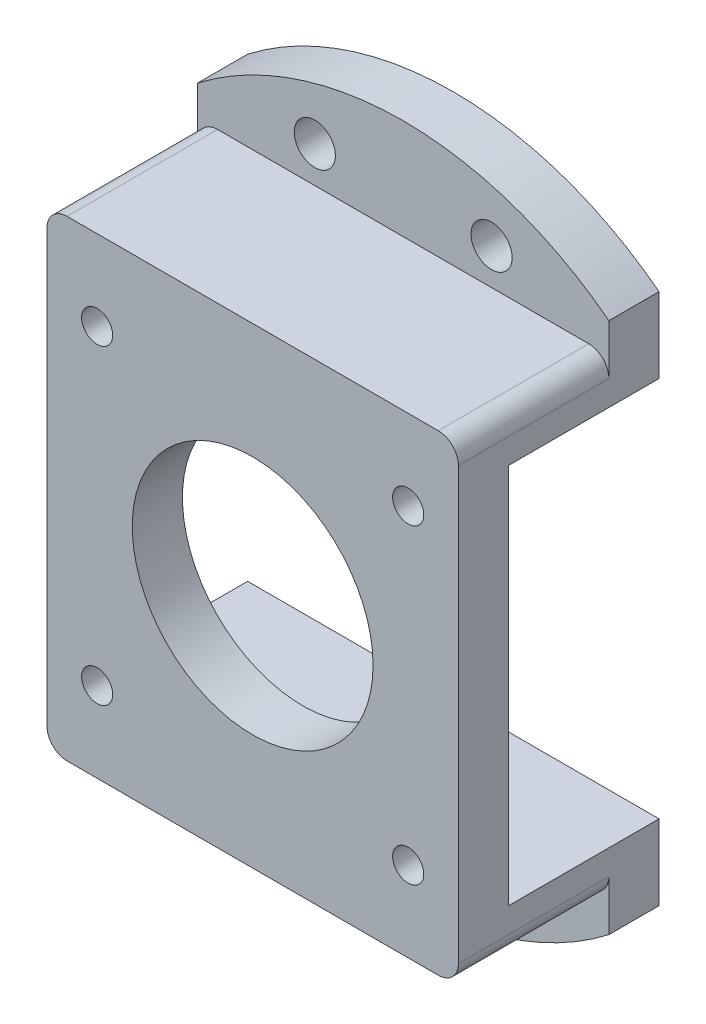
SolidWorks part; units mm, degrees
ref_plane "Front Plane" through (0, 0, 0) normal (0, 0, 1) x (1, 0, 0)
ref_plane "Top Plane" through (0, 0, 0) normal (0, 1, 0) x (1, 0, 0)
ref_plane "Right Plane" through (0, 0, 0) normal (1, 0, 0) x (0, 0, -1)
sketch "Sketch1" plane through (0, 0, 0) normal (0, 0, 1) x (1, 0, 0)
  line L1 (-15.5, -15.5) -> (15.5, -15.5) construction
  line L2 (-15.5, -15.5) -> (-15.5, 15.5) construction
  line L3 (-15.5, 15.5) -> (15.5, 15.5) construction
  line L4 (15.5, -15.5) -> (15.5, 15.5) construction
  line L5 (-15.5, -15.5) -> (15.5, 15.5) construction
  line L6 (-15.5, 15.5) -> (15.5, -15.5) construction
  line L7 (-20.5, -19) -> (20.5, -19)
  line L8 (-20.5, -19) -> (-20.5, 19)
  line L9 (-20.5, 19) -> (20.5, 19)
  line L10 (20.5, -19) -> (20.5, 19)
  line L11 (-20.5, -19) -> (20.5, 19) construction
  line L12 (-20.5, 19) -> (20.5, -19) construction
  circle A0 centre (15.5, 15.5) radius 1.55
  circle A1 centre (-15.5, 15.5) radius 1.55
  circle A2 centre (15.5, -15.5) radius 1.55
  circle A3 centre (-15.5, -15.5) radius 1.55
  circle A4 centre (-15.5, 15.5) radius 2.8 construction
  circle A7 centre (0, 0) radius 12
  point P0 (0, 0)
  point P10 (0, 0)
  dimension "D2" = 3.1
  dimension "D3" = 3.1
  dimension "D4" = 3.1
  dimension "D5" = 3.1
  dimension "D7" = 5.6
  dimension "D8" = 38
  dimension "D9" = 24
  dimension "D1" = 31
  dimension "D6" = 41
extrude "Boss-Extrude1" add sketch "Sketch1" along normal blind 5 contours L7 L10 L9 L8 A4 A3 A2 A0
sketch "Sketch2" plane through (0, 0, 5) normal (0, 0, 1) x (1, 0, 0)
  line L8 (20.5, -19) -> (20.5, 19) construction
  line L9 (-20.5, 19) -> (20.5, 19)
  line L10 (-20.5, 19) -> (-20.5, 23.5)
  line L11 (-20.5, 23.5) -> (20.5, 23.5)
  line L12 (20.5, 19) -> (20.5, 23.5)
  line L13 (-20.5, 19) -> (20.5, 23.5) construction
  line L14 (-20.5, 23.5) -> (20.5, 19) construction
  line L15 (-20.5, 19) -> (20.5, 19) construction
  line L17 (-20.5, -19) -> (20.5, -19)
  line L18 (-20.5, -19) -> (-20.5, -23.5)
  line L19 (-20.5, -23.5) -> (20.5, -23.5)
  line L20 (20.5, -19) -> (20.5, -23.5)
  line L21 (-20.5, -19) -> (20.5, -23.5) construction
  line L22 (-20.5, -23.5) -> (20.5, -19) construction
  point P5 (0, 21.25)
  point P16 (0, -21.25)
  dimension "D1" = 4.5
  dimension "D2" = 4.5
extrude "Boss-Extrude2" add sketch "Sketch2" against normal blind 20
sketch "Sketch3" plane through (0, 0, -15) normal (0, 0, -1) x (-1, 0, 0)
  line L0 (0, 0) -> (0, 28.5) construction
  line L1 (-20.5, 23.5) -> (20.5, 23.5)
  line L2 (-20.5, 23.5) -> (-20.5, 33.5)
  line L3 (-20.5, 33.5) -> (20.5, 33.5)
  line L4 (20.5, 23.5) -> (20.5, 33.5)
  line L5 (-20.5, 23.5) -> (20.5, 33.5) construction
  line L6 (-20.5, 33.5) -> (20.5, 23.5) construction
  line L11 (0, 0) -> (8.807, 27.1051) construction
  line L12 (0, 0) -> (20.5, 0) construction
  line L13 (20.5, -19) -> (20.5, 19) construction
  line L15 (-20.5, -23.5) -> (20.5, -23.5)
  line L16 (-20.5, -23.5) -> (-20.5, -33.5)
  line L17 (-20.5, -33.5) -> (20.5, -33.5)
  line L18 (20.5, -23.5) -> (20.5, -33.5)
  line L19 (-20.5, -23.5) -> (20.5, -33.5) construction
  line L20 (-20.5, -33.5) -> (20.5, -23.5) construction
  circle A2 centre (0, 0) radius 28.5 construction
  circle A3 centre (8.807, 27.1051) radius 2.05
  circle A4 centre (-8.807, 27.1051) radius 2.05
  circle A5 centre (8.807, -27.1051) radius 2.05
  circle A6 centre (-8.807, -27.1051) radius 2.05
  circle A7 centre (0, 0) radius 33.5
  point P5 (0, 28.5)
  point P27 (0, -28.5)
  line M15 (-20.5, -23.5) -> (20.5, -23.5)
  dimension "D1" = 10
  dimension "D2" = 41
  dimension "D4" = 18
  dimension "D3" = 57
  dimension "D5" = 4.1
  dimension "D6" = 10
  dimension "D7" = 41
extrude "Boss-Extrude3" add sketch "Sketch3" against normal blind 5 contours L4 A7 L2 L1 A3 A4 | L16 A7 L18 A6 A5 M15
fillet "Fillet1" radius 2 4 edges at (-20.5, -23.5, -2.5) (20.5, -23.5, -2.5) (-20.5, 23.5, -2.5) (20.5, 23.5, -2.5)
